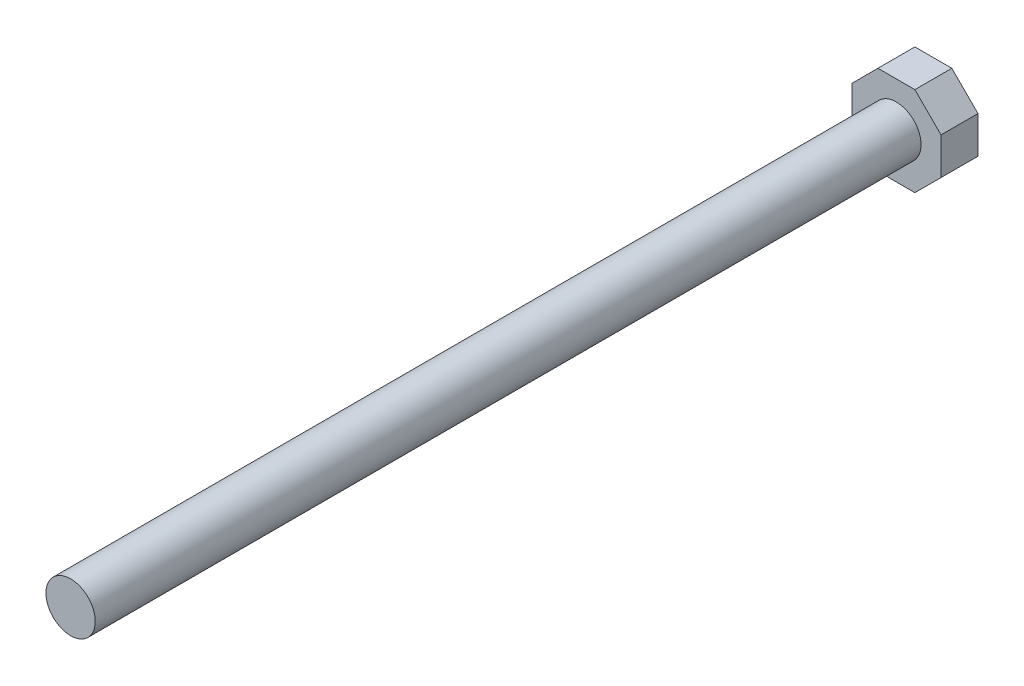
SolidWorks part; units mm, degrees
ref_plane "Ebene vorne" through (0, 0, 0) normal (0, 0, 1) x (1, 0, 0)
ref_plane "Ebene oben" through (0, 0, 0) normal (0, 1, 0) x (1, 0, 0)
ref_plane "Ebene rechts" through (0, 0, 0) normal (1, 0, 0) x (0, 0, -1)
sketch "Skizze1" plane through (0, 0, 0) normal (0, 0, 1) x (1, 0, 0)
  line L0 (-1.777, 0.2852) -> (0.3443, 2.4065)
  line L1 (0.3443, 2.4065) -> (3.3443, 2.4065)
  line L2 (3.3443, 2.4065) -> (5.4656, 0.2852)
  line L3 (5.4656, 0.2852) -> (5.4656, -2.7148)
  line L4 (5.4656, -2.7148) -> (3.3443, -4.8361)
  line L5 (3.3443, -4.8361) -> (0.3443, -4.8361)
  line L6 (0.3443, -4.8361) -> (-1.777, -2.7148)
  line L7 (-1.777, -2.7148) -> (-1.777, 0.2852)
  dimension "D1" = 3
  dimension "D2" = 3
  dimension "D3" = 3
  dimension "D4" = 3
extrude "Aufsatz-Linear austragen1" add sketch "Skizze1" along normal blind 3
sketch "Skizze2" plane through (0, 0, 3) normal (0, 0, 1) x (1, 0, 0)
  line L0 (-1.777, -2.7148) -> (5.4656, 0.2852) construction
  line L1 (0.3443, 2.4065) -> (3.3443, -4.8361) construction
  circle A0 centre (1.8443, -1.2148) radius 2
  point P10 (0.6372, -0.7148)
extrude "Aufsatz-Linear austragen2" add sketch "Skizze2" along normal blind 67
